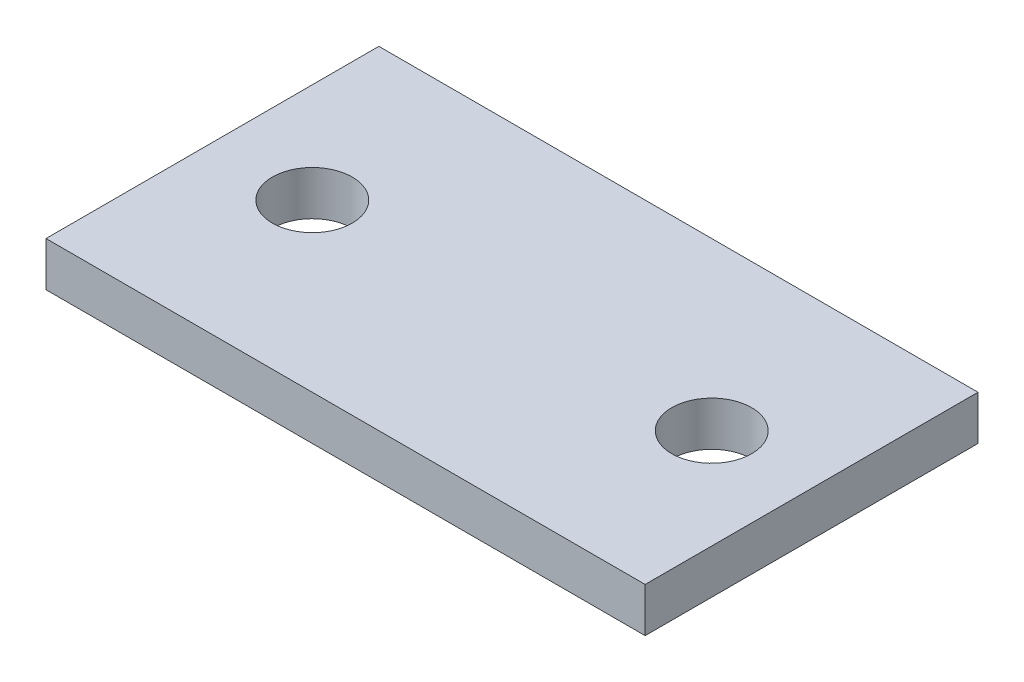
SolidWorks part; units mm, degrees
ref_plane "Plan de face" through (0, 0, 0) normal (0, 0, 1) x (1, 0, 0)
ref_plane "Plan de dessus" through (0, 0, 0) normal (0, 1, 0) x (1, 0, 0)
ref_plane "Plan de droite" through (0, 0, 0) normal (1, 0, 0) x (0, 0, -1)
sketch "Esquisse1" plane through (0, 0, 0) normal (0, 1, 0) x (1, 0, 0)
  line L0 (-6.75, 0) -> (6.75, 0) construction
  line L1 (-6.75, 3.75) -> (6.75, 3.75)
  line L2 (-6.75, 3.75) -> (-6.75, -3.75)
  line L3 (-6.75, -3.75) -> (6.75, -3.75)
  line L4 (6.75, 3.75) -> (6.75, -3.75)
  circle A0 centre (-4.5, 0) radius 0.9
  circle A1 centre (4.5, 0) radius 0.9
  dimension "D5" = 1.8
  dimension "D6" = 1.8
  dimension "D1" = 13.5
  dimension "D2" = 7.5
  dimension "D3" = 4.5
  dimension "D4" = 4.5
extrude "Boss.-Extru.1" add sketch "Esquisse1" along normal blind 1
